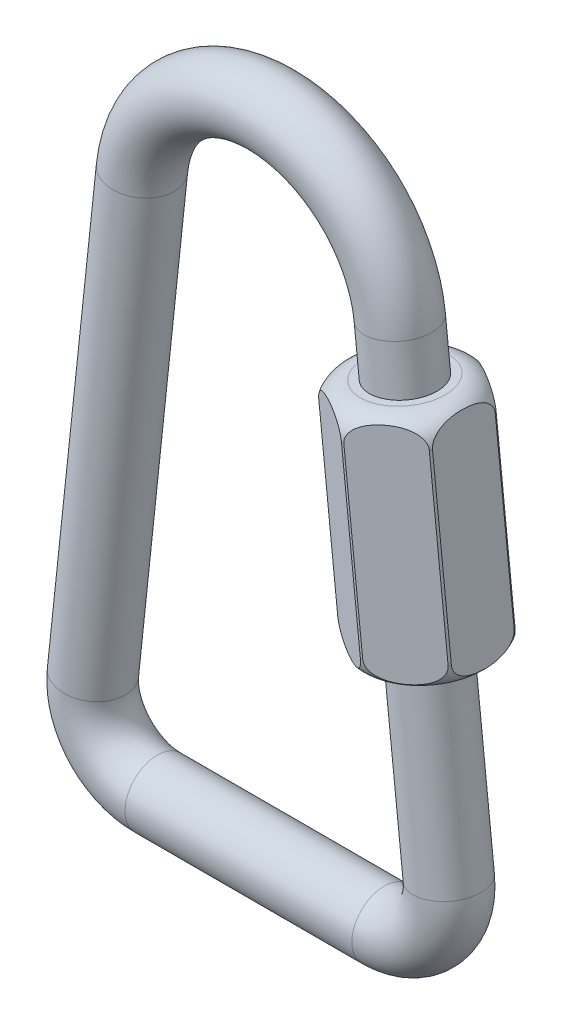
SolidWorks part; units mm, degrees
ref_plane "Front Plane" through (0, 0, 0) normal (0, 0, 1) x (1, 0, 0)
ref_plane "Top Plane" through (0, 0, 0) normal (0, 1, 0) x (1, 0, 0)
ref_plane "Right Plane" through (0, 0, 0) normal (1, 0, 0) x (0, 0, -1)
sketch "Sketch1" plane through (0, 0, 0) normal (1, 0, 0) x (0, 0, -1)
  circle A0 centre (0, 0) radius 2
  dimension "D1" = 4
sketch "Sketch2" plane through (0, 0, 0) normal (0, 0, 1) x (1, 0, 0)
  line L0 (0, 0) -> (-14, 0)
  line L1 (12.1, 0) -> (-12.1, 0) construction
  line L2 (0, -2) -> (0, 2) construction
  line L3 (-17.9776, 4.423) -> (-14.9551, 32.8459)
  line L4 (3.9776, 4.423) -> (0.9551, 32.8459)
  arc A0 (0.9551, 32.8459) -> (-14.9551, 32.8459) centre (-7, 32) ccw
  arc A1 (-14, 0) -> (-17.9776, 4.423) centre (-14, 4) cw
  arc A2 (0, 0) -> (3.9776, 4.423) centre (0, 4) ccw
  dimension "D2" = 40
  dimension "D4" = 16
  dimension "D5" = 4
  dimension "D6" = 4
  dimension "D1" = 14
  dimension "D3" = 7
sweep "Sweep1" add profiles "Sketch1" path "Sketch2"
ref_plane "Plane1" through (0.9551, 32.8459, 0) normal (-0.1057, 0.9944, 0) x (-0.9944, -0.1057, 0)
sketch "Sketch3" plane through (0.9551, 32.8459, 0) normal (-0.1057, 0.9944, 0) x (-0.9944, -0.1057, 0)
  line L0 (16.523, 0) -> (-7.677, 0) construction
  line L1 (-3.5, 2.0207) -> (-3.5, -2.0207)
  line L2 (-3.5, -2.0207) -> (0, -4.0415)
  line L3 (0, -4.0415) -> (3.5, -2.0207)
  line L4 (3.5, -2.0207) -> (3.5, 2.0207)
  line L5 (3.5, 2.0207) -> (0, 4.0415)
  line L6 (0, 4.0415) -> (-3.5, 2.0207)
  circle A0 centre (0, 0) radius 3.5 construction
  dimension "D1" = 7
extrude "Boss-Extrude1" add sketch "Sketch3" along direction (-0.1057, 0.9944, 0) on the side against the normal blind 14 from offset 3 offset against normal yes
sketch "Sketch4" plane through (0, 0, 0) normal (0, 0, 1) x (1, 0, 0)
  line L1 (5.4086, 28.7941) -> (6.5717, 17.8558)
  line L2 (1.2724, 29.8627) -> (4.7528, 30.2328) construction
  line L3 (3.9776, 4.423) -> (0.9551, 32.8459) construction
  line L4 (3.7584, 30.1271) -> (3.3107, 33.4171)
  line L5 (2.7528, 15.9412) -> (6.2331, 16.3113) construction
  line L7 (3.3107, 33.4171) -> (7.6992, 34.0142)
  line L8 (7.6992, 34.0142) -> (9.6874, 16.4831)
  line L9 (9.6874, 16.4831) -> (5.4086, 15.9979)
  line L10 (5.4086, 15.9979) -> (5.2387, 16.2056)
  arc A0 (6.5717, 17.8558) -> (5.2387, 16.2056) centre (5.0801, 17.6972) cw
  arc A1 (5.4086, 28.7941) -> (3.7584, 30.1271) centre (3.917, 28.6355) ccw
  dimension "D1" = 1.5
  dimension "D2" = 4
revolve "Cut-Revolve1" cut sketch "Sketch4" angle 360 about L4
